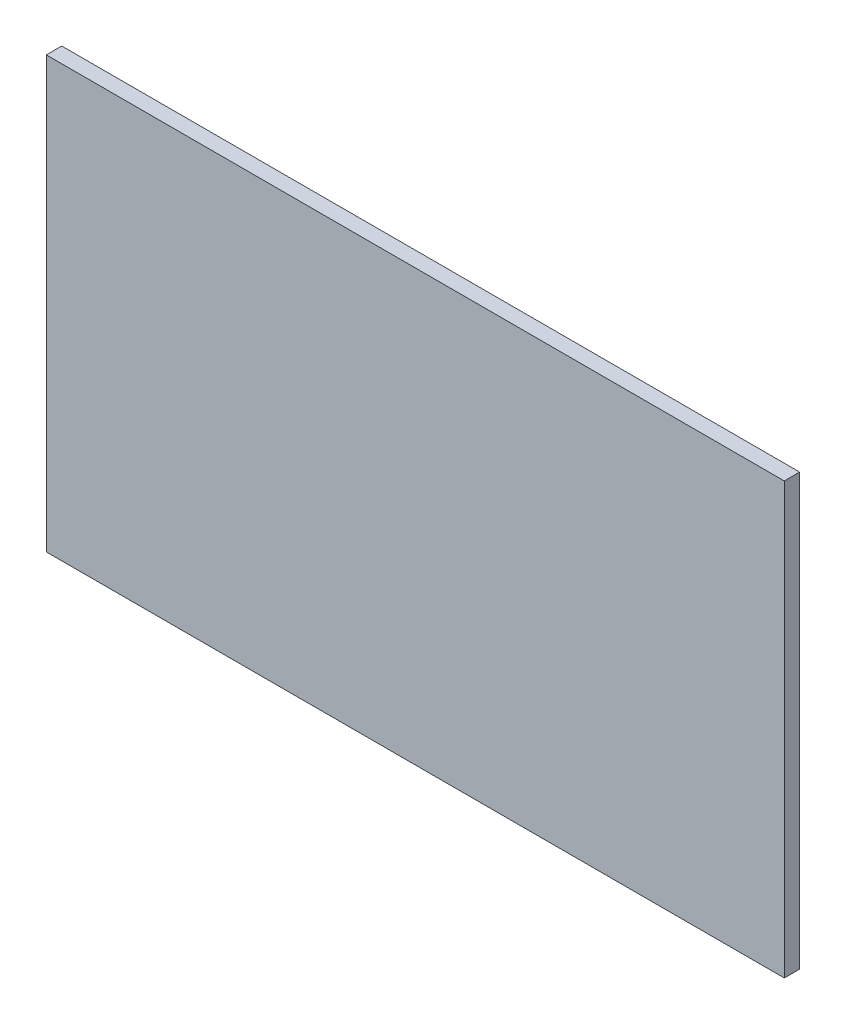
SolidWorks part; units mm, degrees
material "Oak"
ref_plane "Front Plane" through (0, 0, 0) normal (0, 0, 1) x (1, 0, 0)
ref_plane "Top Plane" through (0, 0, 0) normal (0, 1, 0) x (1, 0, 0)
ref_plane "Right Plane" through (0, 0, 0) normal (1, 0, 0) x (0, 0, -1)
sketch "Sketch1" plane through (0, 0, 0) normal (0, 0, 1) x (1, 0, 0)
  line L1 (0, 0) -> (1440, 0)
  line L2 (0, 0) -> (0, 840)
  line L3 (0, 840) -> (1440, 840)
  line L4 (1440, 0) -> (1440, 840)
  dimension "D1" = 840
  dimension "D2" = 1440
extrude "Boss-Extrude1" add sketch "Sketch1" along normal blind 30
